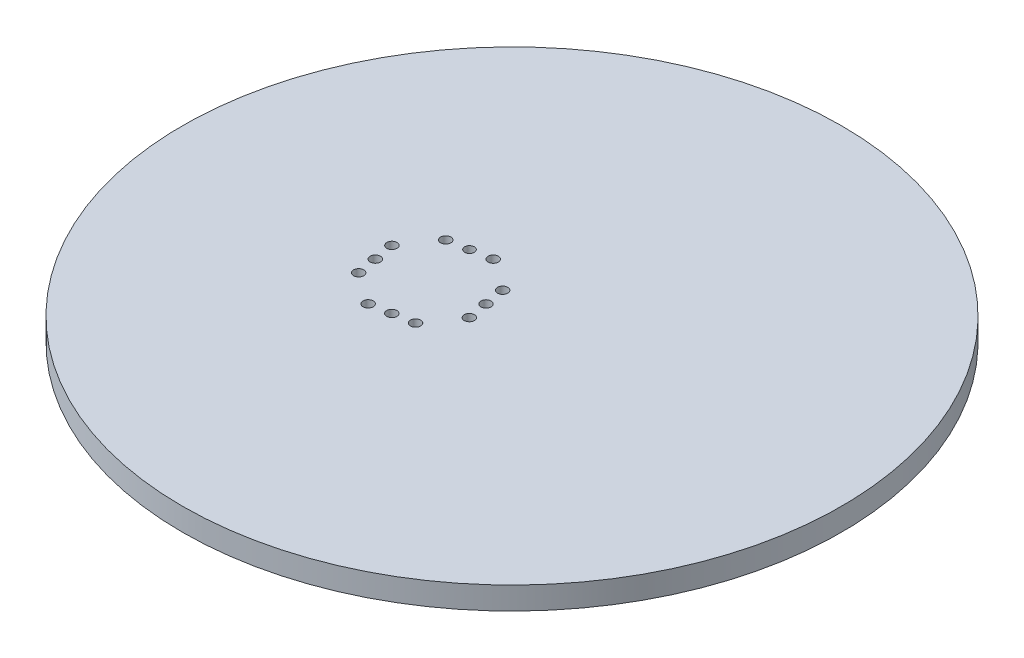
SolidWorks part; units mm, degrees
ref_plane "Front Plane" through (0, 0, 0) normal (0, 0, 1) x (1, 0, 0)
ref_plane "Top Plane" through (0, 0, 0) normal (0, 1, 0) x (1, 0, 0)
ref_plane "Right Plane" through (0, 0, 0) normal (1, 0, 0) x (0, 0, -1)
sketch "Sketch1" plane through (0, 0, 0) normal (0, 1, 0) x (1, 0, 0)
  circle A0 centre (0, 0) radius 48.26
  dimension "D1" = 96.52
extrude "Boss-Extrude1" add sketch "Sketch1" along normal blind 3.302 contours A0
sketch "Sketch2" plane through (0, 3.302, 0) normal (0, 1, 0) x (1, 0, 0)
  circle A0 centre (-17.2239, -2.7938) radius 0.75
  circle A1 centre (-17.7424, 0.1611) radius 0.75
  circle A2 centre (-14.4938, 4.7922) radius 0.75
  circle A3 centre (-16.7055, -5.7486) radius 0.75
  circle A4 centre (-12.0744, -8.9972) radius 0.75
  circle A5 centre (-9.1195, -8.4788) radius 0.75
  circle A6 centre (-6.1647, -7.9603) radius 0.75
  circle A7 centre (-2.9161, -3.3293) radius 0.75
  circle A8 centre (-3.4346, -0.3744) radius 0.75
  circle A9 centre (-3.953, 2.5805) radius 0.75
  circle A10 centre (-8.5841, 5.829) radius 0.75
  circle A11 centre (-11.5389, 5.3106) radius 0.7067
extrude "Cut-Extrude1" cut sketch "Sketch2" against normal blind 7.62
